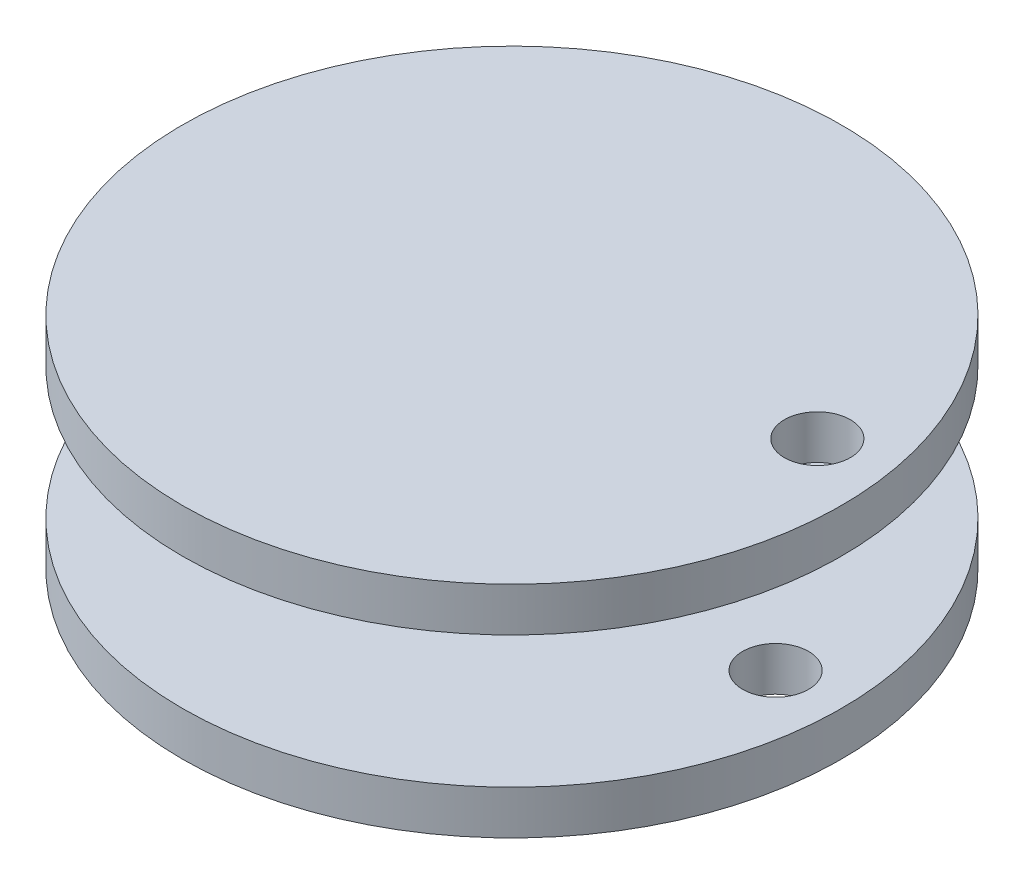
SolidWorks part; units mm, degrees
ref_plane "Front Plane" through (0, 0, 0) normal (0, 0, 1) x (1, 0, 0)
ref_plane "Top Plane" through (0, 0, 0) normal (0, 1, 0) x (1, 0, 0)
ref_plane "Right Plane" through (0, 0, 0) normal (1, 0, 0) x (0, 0, -1)
sketch "Sketch1" plane through (0, 0, 0) normal (0, 1, 0) x (1, 0, 0)
  circle A0 centre (0, 0) radius 75
  circle A1 centre (60, 0) radius 7.5
  dimension "D1" = 150
  dimension "D2" = 15
  dimension "D3" = 60
extrude "Boss-Extrude1" add sketch "Sketch1" along normal blind 10
sketch "Sketch2" plane through (0, 10, 0) normal (0, 1, 0) x (1, 0, 0)
  circle A0 centre (0, 0) radius 7.5
  dimension "D1" = 15
extrude "Boss-Extrude2" add sketch "Sketch2" along normal blind 30
sketch "Sketch3" plane through (0, 40, 0) normal (0, 1, 0) x (1, 0, 0)
  line L0 (0, 0) -> (60, 0) construction
  line L1 (0, 0) -> (59.0885, 10.4189) construction
  circle A0 centre (0, 0) radius 75 construction
  circle A1 centre (0, 0) radius 75
  circle A2 centre (59.0885, 10.4189) radius 7.5
  dimension "D3" = 15
  dimension "D1" = 60
  dimension "D2" = 10
extrude "Boss-Extrude5" add sketch "Sketch3" along normal blind 10
